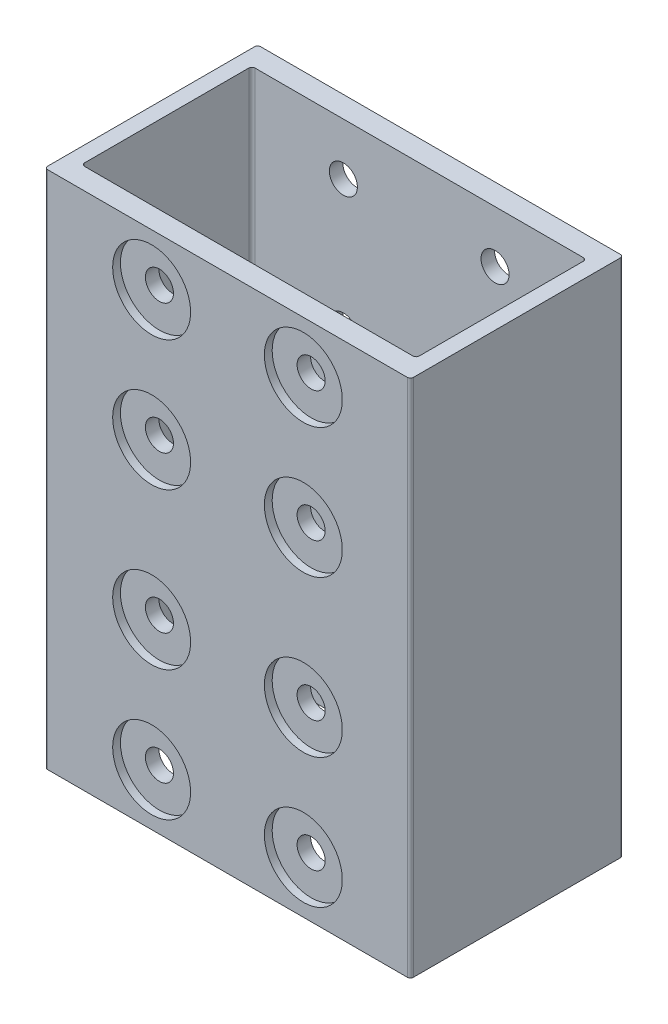
SolidWorks part; units mm, degrees
ref_plane "Front Plane" through (0, 0, 0) normal (0, 0, 1) x (1, 0, 0)
ref_plane "Top Plane" through (0, 0, 0) normal (0, 1, 0) x (1, 0, 0)
ref_plane "Right Plane" through (0, 0, 0) normal (1, 0, 0) x (0, 0, -1)
sketch "Sketch1" plane through (0, 0, 0) normal (0, 1, 0) x (1, 0, 0)
  line L1 (-40.894, -20.828) -> (40.894, -20.828)
  line L2 (-40.894, -20.828) -> (-40.894, 20.828)
  line L3 (-40.894, 20.828) -> (40.894, 20.828)
  line L4 (40.894, -20.828) -> (40.894, 20.828)
  line L5 (-40.894, -20.828) -> (40.894, 20.828) construction
  line L6 (-40.894, 20.828) -> (40.894, -20.828) construction
  line L7 (44.704, -24.13) -> (-44.704, -24.13)
  line L8 (44.704, -24.13) -> (44.704, 24.13)
  line L9 (44.704, 24.13) -> (-44.704, 24.13)
  line L10 (-44.704, -24.13) -> (-44.704, 24.13)
  line L11 (44.704, -24.13) -> (-44.704, 24.13) construction
  line L12 (44.704, 24.13) -> (-44.704, -24.13) construction
  point P0 (0, 0)
  point P6 (0, 0)
  dimension "D1" = 81.788
  dimension "D2" = 41.656
  dimension "D3" = 3.302
  dimension "D4" = 3.81
extrude "Boss-Extrude1" add sketch "Sketch1" along normal blind 127
sketch "Sketch3" plane through (0, 0, 0) normal (0, 0, 1) x (1, 0, 0)
  line L0 (0, 0) -> (0, 127) construction
  line L1 (-44.704, 127) -> (44.704, 127) construction
  line L2 (-44.704, 63.5) -> (44.704, 63.5) construction
  line L3 (-44.704, 127) -> (-44.704, 0) construction
  line L4 (44.704, 127) -> (44.704, 0) construction
  line L5 (-18.542, 114.3) -> (-18.542, 63.5) construction
  circle A0 centre (-18.542, 114.3) radius 3.429
  circle A1 centre (-18.542, 82.55) radius 3.429
  circle A4 centre (18.542, 82.55) radius 3.429
  circle A5 centre (18.542, 114.3) radius 3.429
  circle A6 centre (18.542, 12.7) radius 3.429
  circle A7 centre (18.542, 44.45) radius 3.429
  circle A8 centre (-18.542, 44.45) radius 3.429
  circle A9 centre (-18.542, 12.7) radius 3.429
  point P9 (-18.542, 63.5)
  point P19 (-22.2813, 114.7239)
  dimension "D1" = 6.858
  dimension "D2" = 12.7
  dimension "D3" = 31.75
  dimension "D4" = 18.542
extrude "Cut-Extrude1" cut sketch "Sketch3" against normal through all both and the other way through all
sketch "Sketch5" plane through (0, 0, -24.13) normal (0, 0, -1) x (-1, 0, 0)
  circle A0 centre (-18.542, 114.3) radius 9.525
  circle A1 centre (18.542, 114.3) radius 9.525
  circle A2 centre (-18.542, 82.55) radius 9.525
  circle A3 centre (18.542, 82.55) radius 9.525
  circle A4 centre (18.542, 44.45) radius 9.525
  circle A5 centre (-18.542, 44.45) radius 9.525
  circle A6 centre (-18.542, 12.7) radius 9.525
  circle A7 centre (18.542, 12.7) radius 9.525
  line M17 (44.704, 127) -> (-44.704, 127)
  line M19 (-44.704, 0) -> (44.704, 0)
  line M21 (44.704, 0) -> (44.704, 127)
  line M22 (-44.704, 127) -> (-44.704, 0)
  dimension "D1" = 19.05
extrude "Boss-Extrude3" add sketch "Sketch5" along normal blind 1.905 contours A7 A6 A5 A4 A3 A2 A1 A0 M22 M19 M21 M17
mirror "Mirror3" about plane through (0, 0, 0) normal (0, 0, 1) of "Boss-Extrude3"
fillet "Fillet1" radius 0.762 8 edges at (40.894, 63.5, -20.828) (40.894, 63.5, 20.828) (-40.894, 63.5, 20.828) (-40.894, 63.5, -20.828) (44.704, 63.5, 26.035) (44.704, 63.5, -26.035) (-44.704, 63.5, -26.035) (-44.704, 63.5, 26.035)
